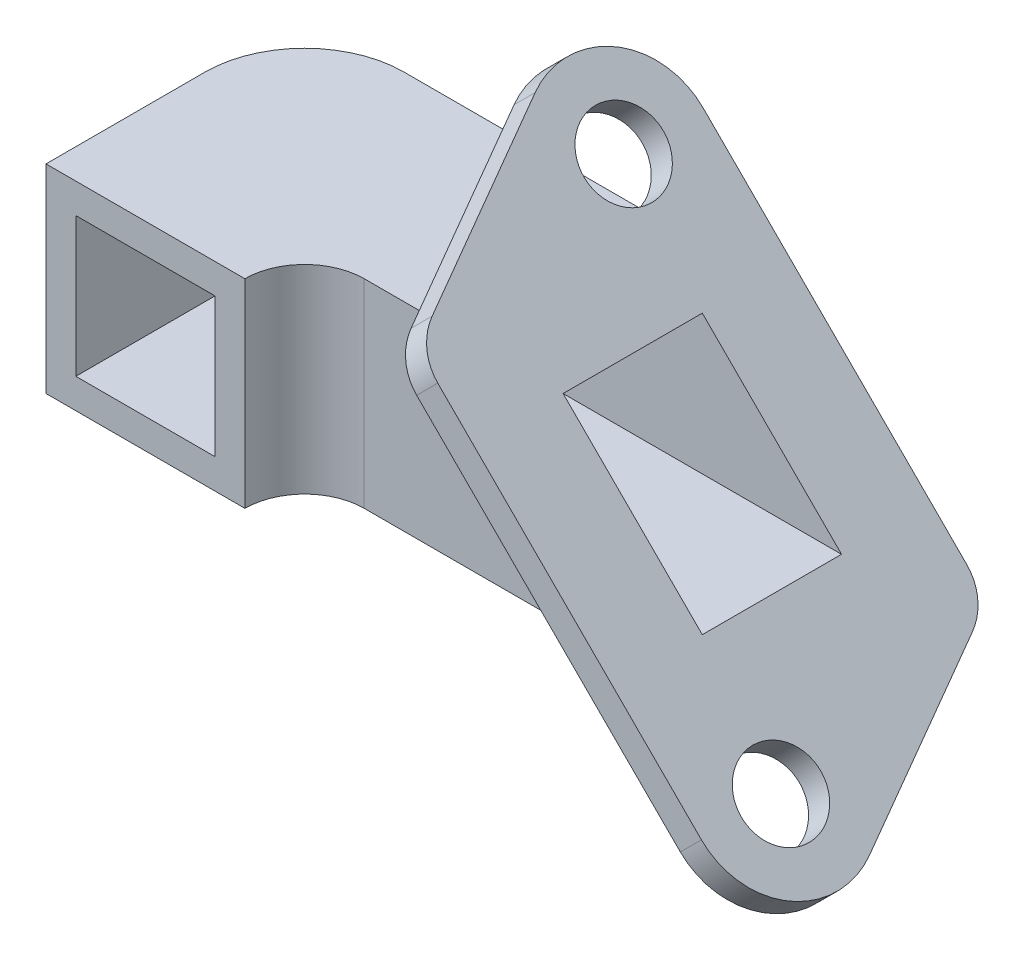
SolidWorks part; units mm, degrees
ref_plane "前基準面" through (0, 0, 0) normal (0, 0, 1) x (1, 0, 0)
ref_plane "上基準面" through (0, 0, 0) normal (0, 1, 0) x (1, 0, 0)
ref_plane "右基準面" through (0, 0, 0) normal (1, 0, 0) x (0, 0, -1)
sketch "草圖1" plane through (0, 0, 0) normal (0, 1, 0) x (1, 0, 0)
  line L0 (56.4558, -20) -> (-48, -20)
  line L1 (-60, -32) -> (-100, -32)
  line L2 (-100, -32) -> (-100, 0)
  line L3 (-80, 20) -> (56.4558, 20)
  line L4 (56.4558, 20) -> (56.4558, -20)
  line L5 (0, -20) -> (0, 20) construction
  arc A0 (-48, -20) -> (-60, -32) centre (-48, -32) ccw
  arc A1 (-100, 0) -> (-80, 20) centre (-80, 0) cw
  dimension "D1" = 12
  dimension "D2" = 20
  dimension "D3" = 40
  dimension "D4" = 100
  dimension "D5" = 40
extrude "伸長1" add sketch "草圖1" along normal mid plane 40
shell "薄殼1" thickness 6
sketch "草圖3" plane through (0, 0, 20) normal (0, 0, 1) x (1, 0, 0)
  line L0 (-31.7481, 31.7481) -> (31.6478, -31.6478)
  line L1 (-48, -20) -> (56.4558, -20) construction
  dimension "D1" = 45
extrude "伸長2" cut sketch "草圖3" against normal through all and the other way through all
sketch "草圖4" plane through (0, 0, 0) normal (0.7071, 0.7071, 0) x (0, 0, -1)
  line L4 (-14, -19.799) -> (14, -19.799) construction
  line L5 (-14, -19.799) -> (14, -19.799)
  line L6 (14, -19.799) -> (14, 19.799) construction
  line L7 (14, -19.799) -> (14, 28.2843)
  line L8 (0, 0) -> (0, 49.9505) construction
  line L9 (0, 0) -> (46.1855, 0) construction
  line L10 (32, -29.9889) -> (32, 45)
  line L11 (8, 58.8564) -> (-27, 38.6491)
  line L12 (-32, 29.9889) -> (-32, -45)
  line L13 (-8, -58.8564) -> (27, -38.6491)
  line L14 (-14, 19.799) -> (-14, -19.799) construction
  line L15 (-14, 28.2843) -> (-14, -19.799)
  line L16 (-20, 28.2843) -> (20, 28.2843) construction
  line L17 (-14, 28.2843) -> (14, 28.2843)
  arc A0 (32, 45) -> (8, 58.8564) centre (16, 45) ccw
  arc A1 (-27, 38.6491) -> (-32, 29.9889) centre (-22, 29.9889) ccw
  circle A2 centre (16, 45) radius 8
  arc A3 (-32, -45) -> (-8, -58.8564) centre (-16, -45) ccw
  arc A4 (27, -38.6491) -> (32, -29.9889) centre (22, -29.9889) ccw
  circle A5 centre (-16, -45) radius 8
  dimension "D1" = 16
  dimension "D2" = 10
  dimension "D3" = 16
  dimension "D5" = 16
  dimension "D6" = 10
  dimension "D7" = 16
  dimension "D8" = 16
  dimension "D10" = 45
  dimension "D4" = 16
  dimension "D9" = 45
  dimension "D11" = 60
  dimension "D12" = 60
extrude "伸長5" add sketch "草圖4" against normal blind 6
